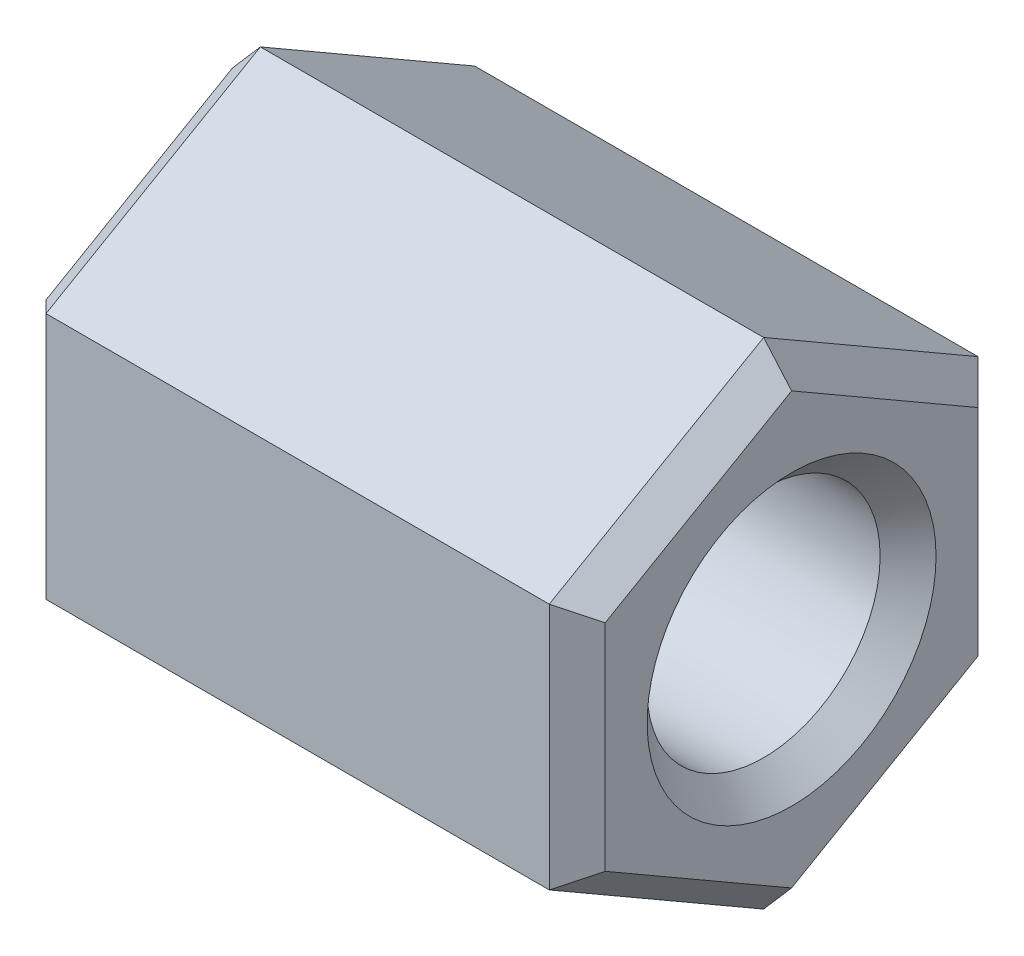
SolidWorks part; units mm, degrees
ref_plane "前视基准面" through (0, 0, 0) normal (1, 0, 0) x (0, 1, 0)
ref_plane "上视基准面" through (0, 0, 0) normal (0, 0, 1) x (0, 1, 0)
ref_plane "右视基准面" through (0, 0, 0) normal (0, 1, 0) x (-1, 0, 0)
other "Configuration Table"
sketch "草图1" plane through (0, 0, 0) normal (1, 0, 0) x (0, 1, 0)
  line L0 (0, 0) -> (2.6558, 0) construction
  line L1 (2.6558, 0) -> (1.3279, 2.3)
  line L2 (1.3279, 2.3) -> (-1.3279, 2.3)
  line L3 (-1.3279, 2.3) -> (-2.6558, 0)
  line L4 (-2.6558, 0) -> (-1.3279, -2.3)
  line L5 (-1.3279, -2.3) -> (1.3279, -2.3)
  line L6 (1.3279, -2.3) -> (2.6558, 0)
  circle A0 centre (0, 0) radius 1.25
  circle A1 centre (0, 0) radius 2.3 construction
  dimension "D1" = 2.5
  dimension "D2" = 4.6
extrude "凸台-拉伸1" add sketch "草图1" along normal blind 6
chamfer "倒角1" distance 0.3 angle 45 14 edges at (0, 0, -1.25) (0, 1.9919, 1.15) (0, 0, 2.3) (0, -1.9919, 1.15) (0, -1.9919, -1.15) (0, 0, -2.3) (0, 1.9919, -1.15) (6, 0, -1.25) (6, 0, -2.3) (6, -1.9919, -1.15) (6, -1.9919, 1.15) (6, 0, 2.3) (6, 1.9919, 1.15) (6, 1.9919, -1.15)
